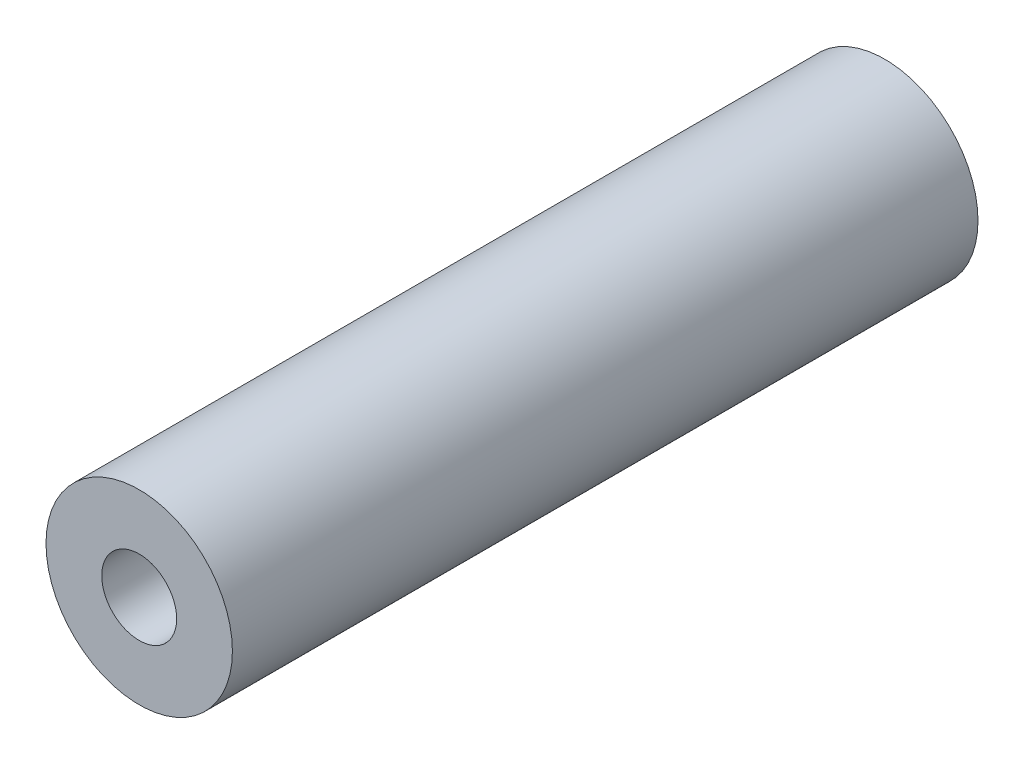
SolidWorks part; units mm, degrees
ref_plane "Front Plane" through (0, 0, 0) normal (0, 0, 1) x (1, 0, 0)
ref_plane "Top Plane" through (0, 0, 0) normal (0, 1, 0) x (1, 0, 0)
ref_plane "Right Plane" through (0, 0, 0) normal (1, 0, 0) x (0, 0, -1)
sketch "Sketch1" plane through (0, 0, 0) normal (0, 0, 1) x (1, 0, 0)
  circle A0 centre (0, 0) radius 2.5527
  circle A1 centre (0, 0) radius 6.35
  dimension "D1" = 5.1054
  dimension "D2" = 12.7
extrude "Boss-Extrude1" add sketch "Sketch1" along normal mid plane 50.8
